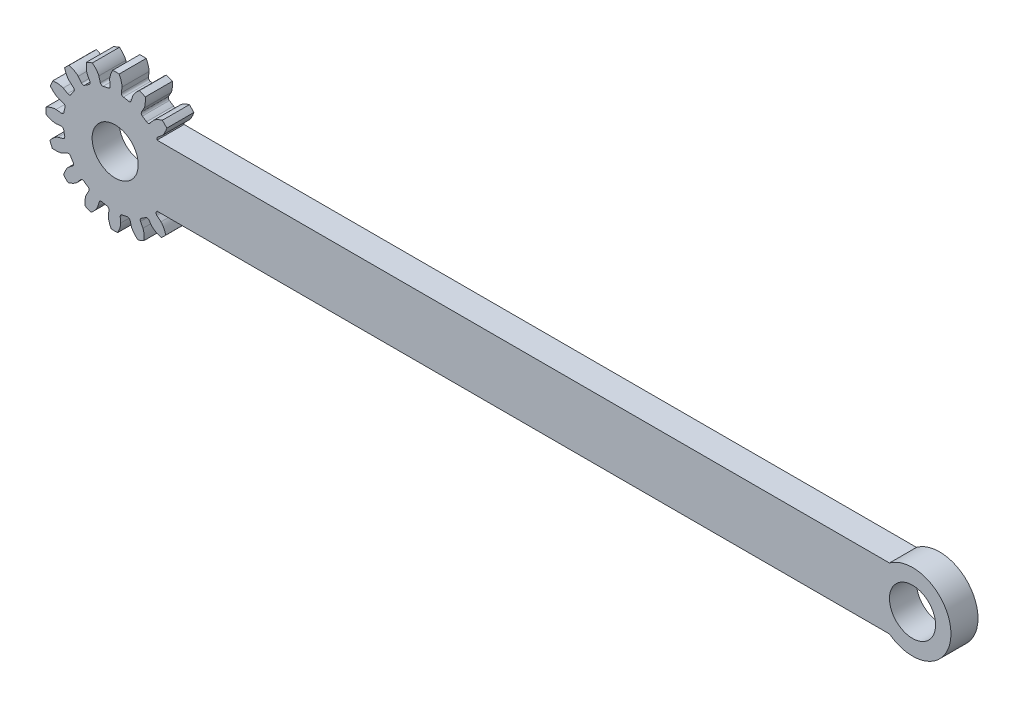
SolidWorks part; units mm, degrees
ref_plane "Front Plane" through (0, 0, 0) normal (0, 0, 1) x (1, 0, 0)
ref_plane "Top Plane" through (0, 0, 0) normal (0, 1, 0) x (1, 0, 0)
ref_plane "Right Plane" through (0, 0, 0) normal (1, 0, 0) x (0, 0, -1)
sketch "Sketch1" plane through (0, 0, 0) normal (0, 0, 1) x (1, 0, 0)
  line L1 (12.7988, -6.35) -> (159.9195, -6.35)
  line L3 (12.7988, 6.35) -> (159.9195, 6.35)
  arc A1 (159.9195, -6.35) -> (159.9195, 6.35) centre (164.682, 0) ccw
  arc A2 (12.7988, 6.35) -> (12.7988, -6.35) centre (0, 0) ccw
  dimension "D4" = 15.875
  dimension "D2" = 28.575
  dimension "D1" = 12.7
extrude "Boss-Extrude1" add sketch "Sketch1" along normal blind 5.588
sketch "Sketch3" plane through (0, 0, 5.588) normal (0, 0, 1) x (1, 0, 0)
  line L0 (0, 0) -> (10.3045, 2.9396) construction
  line L1 (10.3045, 2.9396) -> (11.8238, 3.373)
  line L2 (0, 0) -> (10.6697, 0.9912) construction
  line L3 (10.6697, 0.9912) -> (12.2428, 1.1373)
  line L4 (0, 0) -> (19.1436, 0) construction
  circle A0 centre (0, 0) radius 14.2875 construction
  circle A1 centre (0, 0) radius 12.7 construction
  circle A2 centre (0, 0) radius 12.2955 construction
  circle A3 centre (0, 0) radius 10.7156 construction
  arc A6 (10.3045, 2.9396) -> (10.6697, 0.9912) centre (0, 0) cw
  arc A7 (13.4917, 4.7018) -> (14.2787, 0.5026) centre (0, 0) cw
  spline S0 degree 4 poles (11.8238, 3.373) (11.8268, 3.3739) (11.8354, 3.3766) (11.8513, 3.3821) (11.8772, 3.3918) (11.9098, 3.4051) (11.9516, 3.4234) (12.0003, 3.4463) (12.0533, 3.473) (12.1104, 3.5037) (12.1667, 3.5357) (12.2225, 3.5689) (12.2775, 3.6031) (12.3435, 3.6459) (12.4219, 3.6992) (12.5123, 3.7642) (12.6132, 3.8411) (12.7145, 3.9229) (12.8128, 4.0062) (12.9104, 4.0936) (13.0037, 4.1803) (13.099, 4.2737) (13.186, 4.3615) (13.2815, 4.4634) (13.358, 4.5466) (13.4567, 4.6602) (13.5144, 4.7283) (13.5811, 4.8094) (13.6104, 4.846) (13.6284, 4.8686) knots 0 0 0 0 0 0.005377 0.015084 0.028532 0.04661 0.064855 0.092111 0.119476 0.146842 0.174209 0.201575 0.228941 0.256307 0.307035 0.361767 0.4165 0.471232 0.525964 0.580697 0.635429 0.690161 0.744894 0.799626 0.854358 0.909091 0.954545 1 1 1 1 1 construction
  spline S1 degree 4 poles (11.8238, 3.373) (11.8268, 3.3739) (11.8354, 3.3766) (11.8513, 3.3821) (11.8772, 3.3918) (11.9098, 3.4051) (11.9516, 3.4234) (12.0003, 3.4463) (12.0533, 3.473) (12.1104, 3.5037) (12.1667, 3.5357) (12.2225, 3.5689) (12.2775, 3.6031) (12.3435, 3.6459) (12.4219, 3.6992) (12.5123, 3.7642) (12.6132, 3.8411) (12.7145, 3.9229) (12.8128, 4.0062) (12.9104, 4.0936) (13.0037, 4.1803) (13.099, 4.2737) (13.186, 4.3615) (13.2815, 4.4634) (13.358, 4.5466) (13.4353, 4.6355) (13.4727, 4.6792) (13.4917, 4.7018) knots 0 0 0 0 0 0.005377 0.015084 0.028532 0.04661 0.064855 0.092111 0.119476 0.146842 0.174209 0.201575 0.228941 0.256307 0.307035 0.361767 0.4165 0.471232 0.525964 0.580697 0.635429 0.690161 0.744894 0.799626 0.854358 0.909091 0.909091 0.909091 0.909091 0.909091
  spline S2 degree 4 poles (12.2428, 1.1373) (12.2459, 1.1376) (12.2548, 1.1381) (12.2717, 1.1388) (12.2993, 1.1391) (12.3346, 1.1385) (12.3801, 1.1366) (12.4339, 1.1329) (12.493, 1.1271) (12.5572, 1.1192) (12.6214, 1.1098) (12.6853, 1.0991) (12.749, 1.0871) (12.8261, 1.0711) (12.9184, 1.0498) (13.0262, 1.0219) (13.1482, 0.9868) (13.2722, 0.9472) (13.3939, 0.9051) (13.5166, 0.8591) (13.635, 0.812) (13.7575, 0.7595) (13.8704, 0.7091) (13.9964, 0.6487) (14.0978, 0.5988) (14.231, 0.5288) (14.3094, 0.4861) (14.401, 0.4347) (14.4415, 0.4112) (14.4665, 0.3967) knots 0 0 0 0 0 0.005377 0.015084 0.028532 0.04661 0.064855 0.092111 0.119476 0.146842 0.174209 0.201575 0.228941 0.256307 0.307035 0.361767 0.4165 0.471232 0.525964 0.580697 0.635429 0.690161 0.744894 0.799626 0.854358 0.909091 0.954545 1 1 1 1 1 construction
  spline S3 degree 4 poles (12.2428, 1.1373) (12.2459, 1.1376) (12.2548, 1.1381) (12.2717, 1.1388) (12.2993, 1.1391) (12.3346, 1.1385) (12.3801, 1.1366) (12.4339, 1.1329) (12.493, 1.1271) (12.5572, 1.1192) (12.6214, 1.1098) (12.6853, 1.0991) (12.749, 1.0871) (12.8261, 1.0711) (12.9184, 1.0498) (13.0262, 1.0219) (13.1482, 0.9868) (13.2722, 0.9472) (13.3939, 0.9051) (13.5166, 0.8591) (13.635, 0.812) (13.7575, 0.7595) (13.8704, 0.7091) (13.9964, 0.6487) (14.0978, 0.5988) (14.2021, 0.5439) (14.2528, 0.5168) (14.2787, 0.5026) knots 0 0 0 0 0 0.005377 0.015084 0.028532 0.04661 0.064855 0.092111 0.119476 0.146842 0.174209 0.201575 0.228941 0.256307 0.307035 0.361767 0.4165 0.471232 0.525964 0.580697 0.635429 0.690161 0.744894 0.799626 0.854358 0.909091 0.909091 0.909091 0.909091 0.909091
  dimension "D1" = 28.575
  dimension "D2" = 25.4
  dimension "D3" = 24.591
  dimension "D4" = 21.4312
  dimension "D5" = 12.2955
  dimension "D6" = 14.2875
  dimension "D7" = 12.2955
  dimension "D8" = 14.2875
  dimension "D9" = 10.615
  dimension "D10" = 15.922
extrude "Cut-Extrude1" cut sketch "Sketch3" against normal through all
fillet "Fillet1" radius 0.4962 2 edges at (10.3045, 2.9396, 2.794) (10.6697, 0.9912, 2.794)
pattern_circular "CirPattern1" count 16 over 360 about axis through (0, 0, 5.588) along (0, 0, 1) of "Fillet1", "Cut-Extrude1"
ref_plane "Plane1" through (10.16, 0, 0) normal (1, 0, 0) x (0, 0, -1)
sketch "Sketch4" plane through (10.16, 0, 0) normal (1, 0, 0) x (0, 0, -1)
  line L6 (0, 6.35) -> (-5.588, 6.35)
  line L8 (0, 6.35) -> (0, -6.35)
  line L9 (0, -6.35) -> (-5.588, -6.35)
  line L10 (-5.588, 6.35) -> (-5.588, -6.35)
  line L11 (0, 6.35) -> (-5.588, -6.35) construction
  line L12 (0, -6.35) -> (-5.588, 6.35) construction
  point P0 (-2.794, 0)
  dimension "D1" = 5.588
  dimension "D2" = 12.7
extrude "Boss-Extrude2" add sketch "Sketch4" against normal mid plane 10.16
sketch "Sketch5" plane through (0, 0, 5.588) normal (0, 0, 1) x (1, 0, 0)
  circle A0 centre (0, 0) radius 4.7625
  circle A1 centre (164.682, 0) radius 4.7625
  dimension "D1" = 9.525
extrude "Cut-Extrude2" cut sketch "Sketch5" against normal through all
equation "\"DiametralPitch\"= 16"
equation "\"NumTeeth\"= 16"
equation "\"PressureAngle\"= 14.5deg"
equation "\"Addendum\"= 1 / \"DiametralPitch\""
equation "\"Dedendum\"= 1.25 / \"DiametralPitch\""
equation "\"WorkingDepth\"= 2 / \"DiametralPitch\""
equation "\"WholeDepth\"= 2.25 / \"DiametralPitch\""
equation "\"Clearance\"= 0.25 / \"DiametralPitch\""
equation "\"ToothThickness\"= 1.5708 / \"DiametralPitch\""
equation "\"CircularPitch\"= pi / \"DiametralPitch\""
equation "\"PitchCircle\"= \"NumTeeth\" / \"DiametralPitch\""
equation "\"OutsideDiameter\"= ( \"NumTeeth\" + 2 ) / \"DiametralPitch\""
equation "\"Fillet\"= \"Clearance\" * cos ( \"PressureAngle\" ) * tan ( ( 90 + \"PressureAngle\" ) / 2 )"
equation "\"AddendumCircle\"= \"PitchCircle\" + ( 2 * \"Addendum\" )"
equation "\"DedendumCircle\"= \"PitchCircle\" - ( 2 * \"Dedendum\" )"
equation "\"BaseCircle\"= \"PitchCircle\" * cos ( \"PressureAngle\" )"
equation "\"PitchAngle\"= 360deg / \"NumTeeth\""
equation "\"Alpha\"= sqr ( \"PitchCircle\" ^ 2 - \"BaseCircle\" ^ 2 ) / \"BaseCircle\" * 180 / PI - \"PressureAngle\""
equation "\"Beta\"= ( \"PitchAngle\" / 4 - \"Alpha\" )"
equation "\"Phi\"= sqr ( ( \"AddendumCircle\" / 2 ) ^ 2 - ( \"BaseCircle\" / 2 ) ^ 2 ) / ( \"BaseCircle\" / 2 )"
equation "\"D2@Sketch1\"= \"OutsideDiameter\""
equation "\"D1@Sketch3\"=\"OutsideDiameter\""
equation "\"D2@Sketch3\"=\"PitchCircle\""
equation "\"D3@Sketch3\"=\"BaseCircle\""
equation "\"D4@Sketch3\"=\"DedendumCircle\""
equation "\"D1@Fillet1\"=\"Fillet\""
equation "\"D1@CirPattern1\"=\"NumTeeth\""
